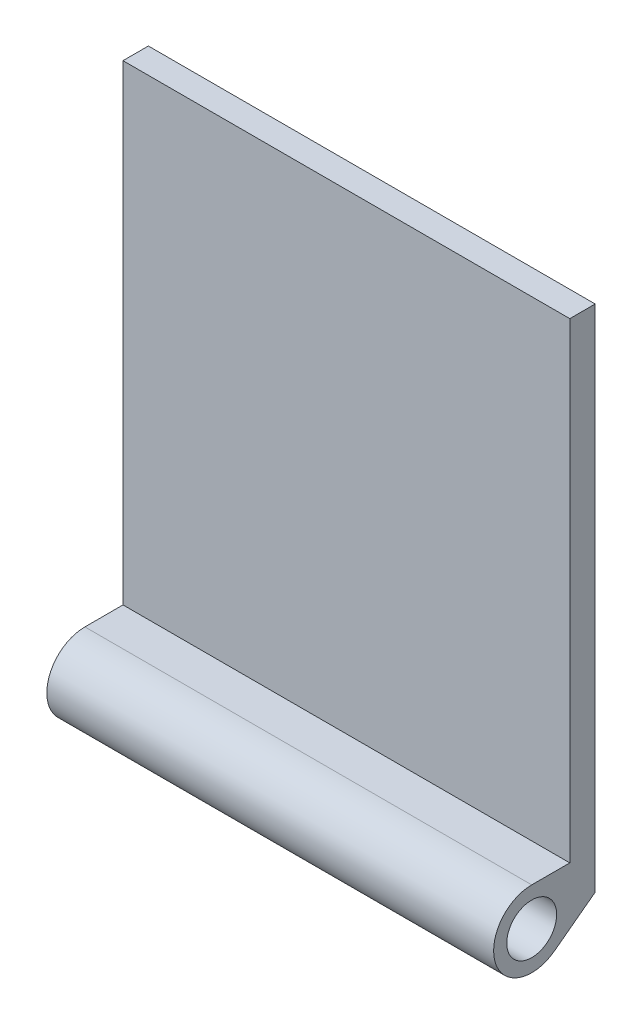
SolidWorks part; units mm, degrees
ref_plane "Alzado" through (0, 0, 0) normal (0, 0, 1) x (1, 0, 0)
ref_plane "Planta" through (0, 0, 0) normal (0, 1, 0) x (1, 0, 0)
ref_plane "Vista lateral" through (0, 0, 0) normal (1, 0, 0) x (0, 0, -1)
sketch "Croquis1" plane through (0, 0, 0) normal (0, 0, 1) x (1, 0, 0)
  line L1 (0.9194, 8.0901) -> (27.3194, 8.0901)
  line L2 (0.9194, 8.0901) -> (0.9194, -22.0099)
  line L3 (0.9194, -22.0099) -> (27.3194, -22.0099)
  line L4 (27.3194, 8.0901) -> (27.3194, -22.0099)
  dimension "D1" = 30.1
  dimension "D2" = 26.4
extrude "Saliente-Extruir1" add sketch "Croquis1" along normal blind 1.5
sketch "Croquis3" plane through (27.3194, 0, 0) normal (1, 0, 0) x (0, 0, -1)
  line L0 (-1.5, -22.0099) -> (-1.5, 8.0901) construction
  line L1 (0, -22.0099) -> (-2.4001, -23.8097)
  line L2 (-3.75, -19.7596) -> (-1.5, -19.7596)
  line L3 (-1.5, -19.7596) -> (0, -22.0099)
  arc A0 (-3.75, -19.7596) -> (-2.4001, -23.8097) centre (-3.75, -22.0096) ccw
  circle A1 centre (-3.75, -22.0096) radius 1.475
  dimension "D1" = 4.5
  dimension "D2" = 2.25
  dimension "D3" = 2.95
extrude "Saliente-Extruir3" add sketch "Croquis3" against normal up to surface (26.4 mm away) up to face at (0.9194, -6.9599, 0.75)
